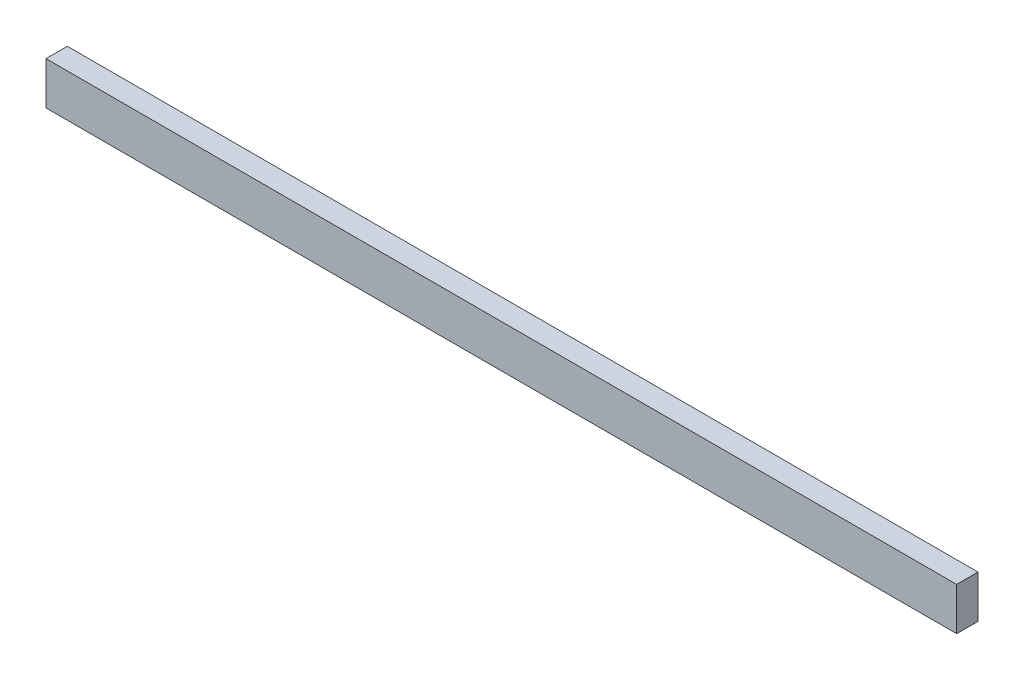
SolidWorks part; units mm, degrees
ref_plane "Front Plane" through (0, 0, 0) normal (0, 0, 1) x (1, 0, 0)
ref_plane "Top Plane" through (0, 0, 0) normal (0, 1, 0) x (1, 0, 0)
ref_plane "Right Plane" through (0, 0, 0) normal (1, 0, 0) x (0, 0, -1)
sketch "Sketch1" plane through (0, 0, 0) normal (0, 0, 1) x (1, 0, 0)
  line L0 (549.8213, 30.3497) -> (549.8213, -20.4503)
  line L1 (549.8213, -20.4503) -> (-533.3224, -20.4503)
  line L2 (549.8213, 30.3497) -> (-533.3224, 30.3497)
  line L3 (-533.3224, 30.3497) -> (-533.3224, -20.4503)
extrude "Boss-Extrude1" add sketch "Sketch1" along normal blind 25.4
ref_plane "Plane1" through (0, 0, -101.6) normal (0, 0, 1) x (1, 0, 0)
